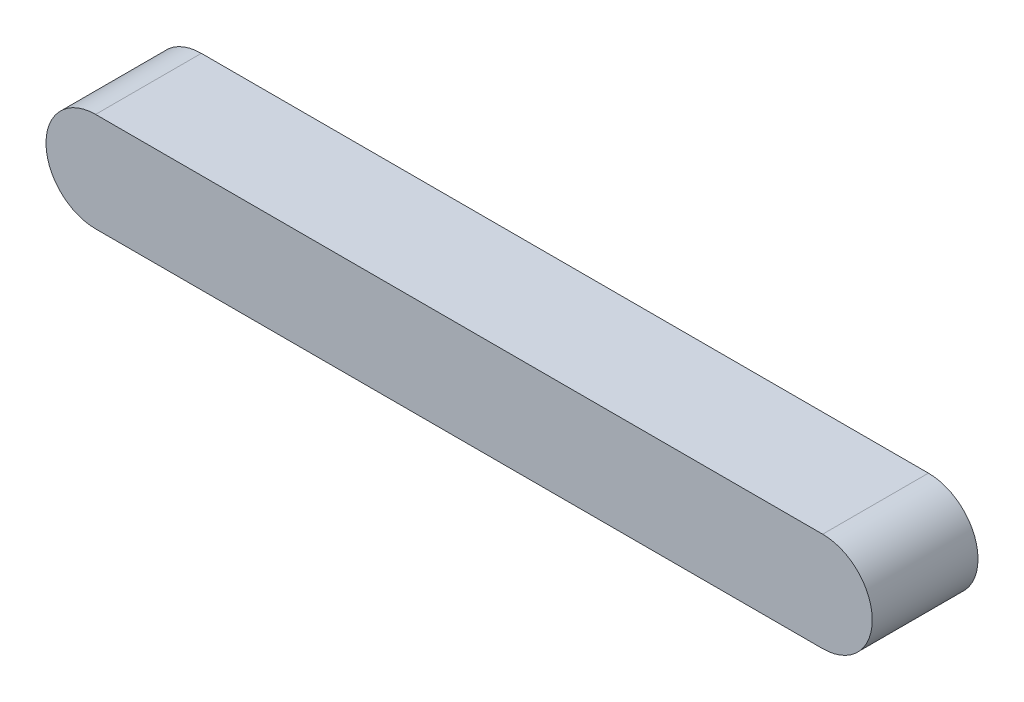
SolidWorks part; units mm, degrees
ref_plane "Piano frontale" through (0, 0, 0) normal (0, 0, 1) x (1, 0, 0)
ref_plane "Piano superiore" through (0, 0, 0) normal (0, 1, 0) x (1, 0, 0)
ref_plane "Piano destro" through (0, 0, 0) normal (1, 0, 0) x (0, 0, -1)
sketch "Schizzo1" plane through (0, 0, 0) normal (0, 0, 1) x (1, 0, 0)
  line L0 (0, 0) -> (22, 0) construction
  line L1 (0, 1.5) -> (22, 1.5)
  line L2 (0, -1.5) -> (22, -1.5)
  arc A0 (0, 1.5) -> (0, -1.5) centre (0, 0) ccw
  arc A1 (22, -1.5) -> (22, 1.5) centre (22, 0) ccw
  point P3 (11, 0)
  point P8 (-1.5, 0)
  point P9 (23.5, 0)
  dimension "D1" = 25
  dimension "D2" = 3
extrude "Estrusione-Estrusione1" add sketch "Schizzo1" along normal blind 3.2
